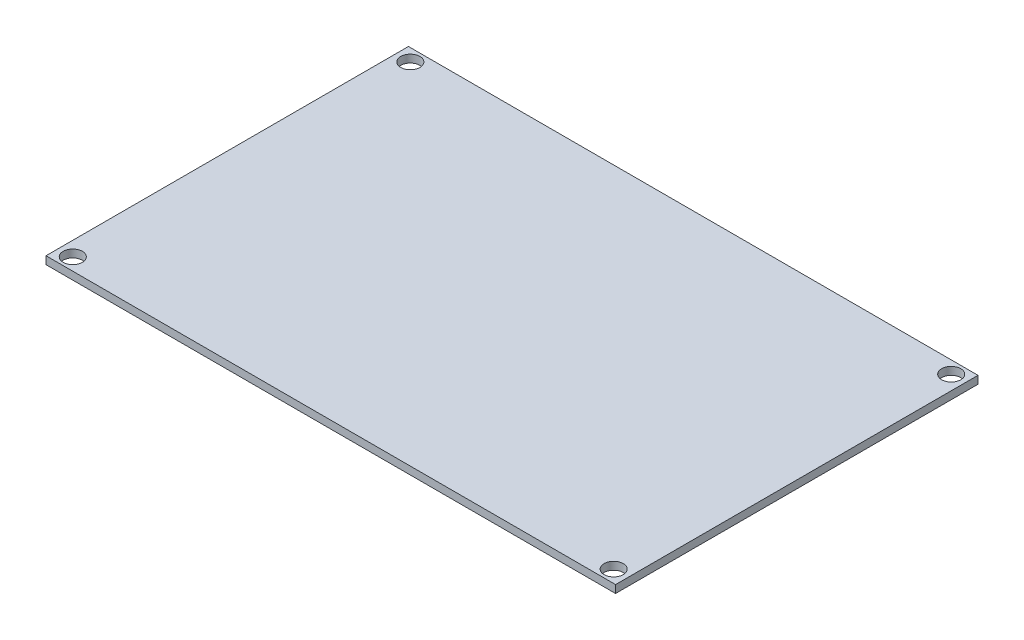
SolidWorks part; units mm, degrees
ref_plane "Ön Düzlem" through (0, 0, 0) normal (0, 0, 1) x (1, 0, 0)
ref_plane "Üst Düzlem" through (0, 0, 0) normal (0, 1, 0) x (1, 0, 0)
ref_plane "Sağ Düzlem" through (0, 0, 0) normal (1, 0, 0) x (0, 0, -1)
sketch "Çizim1" plane through (0, 0, 0) normal (0, 1, 0) x (1, 0, 0)
  line L1 (-55, -35) -> (55, -35)
  line L2 (-55, -35) -> (-55, 35)
  line L3 (-55, 35) -> (55, 35)
  line L4 (55, -35) -> (55, 35)
  line L5 (-55, -35) -> (55, 35) construction
  line L6 (-55, 35) -> (55, -35) construction
  point P0 (0, 0)
extrude "Yükseklik-Ekstrüzyon1" add sketch "Çizim1" along normal blind 1.5
sketch "Çizim2" plane through (0, 1.5, 0) normal (0, 1, 0) x (1, 0, 0)
  circle A0 centre (-52.2322, 32.5959) radius 1.85
  circle A2 centre (52.2322, 32.5959) radius 1.85
  circle A3 centre (52.2322, -32.5959) radius 1.85
  circle A4 centre (-52.2322, -32.5959) radius 1.85
  dimension "D1" = 3.7
extrude "Kes-Ekstrüzyon1" cut sketch "Çizim2" against normal blind 1.5
